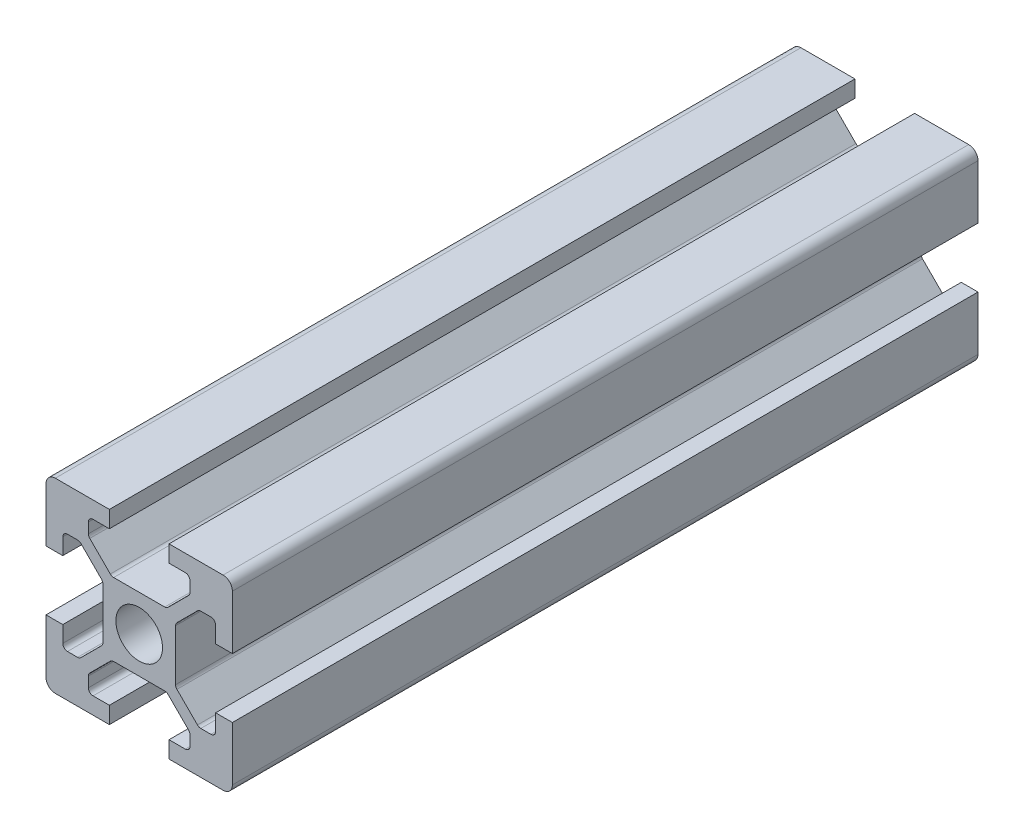
SolidWorks part; units mm, degrees
material "1060 Alloy"
ref_plane "Front Plane" through (0, 0, 0) normal (0, 0, 1) x (1, 0, 0)
ref_plane "Top Plane" through (0, 0, 0) normal (0, 1, 0) x (1, 0, 0)
ref_plane "Right Plane" through (0, 0, 0) normal (1, 0, 0) x (0, 0, -1)
sketch "Sketch1" plane through (0, 0, 0) normal (0, 0, 1) x (1, 0, 0)
  line L0 (20, 0) -> (-8.059, 28.059) construction
  line L1 (0, 0) -> (6.8, 0)
  line L2 (0, 0) -> (0, 6.8)
  line L3 (0, 20) -> (6.8, 20)
  line L4 (20, 0) -> (20, 6.8)
  line L5 (6.8, 20) -> (6.8, 18.2)
  line L6 (20, 20) -> (8.2322, 8.2322) construction
  line L7 (12.95, 6.1) -> (7.05, 6.1)
  line L8 (13.9, 7.05) -> (13.9, 12.95)
  line L9 (12.95, 13.9) -> (7.05, 13.9)
  line L10 (6.1, 7.05) -> (6.1, 12.95)
  line L11 (13.9, 6.1) -> (6.1, 13.9) construction
  line L12 (13.9, 13.9) -> (6.1, 6.1) construction
  line L13 (4.55, 16.4) -> (7.05, 13.9)
  line L14 (13.2, 18.2) -> (13.2, 20)
  line L15 (1.8, 6.8) -> (0, 6.8)
  line L16 (0, 13.2) -> (0, 20)
  line L17 (0, 13.2) -> (1.8, 13.2)
  line L18 (10, 10) -> (10, 13.9) construction
  line L19 (16.4, 4.55) -> (13.9, 7.05)
  line L20 (4.55, 16.4) -> (4.55, 18.2)
  line L21 (4.55, 18.2) -> (6.8, 18.2)
  line L22 (13.2, 18.2) -> (15.45, 18.2)
  line L23 (15.45, 18.2) -> (15.45, 16.4)
  line L24 (15.45, 16.4) -> (12.95, 13.9)
  line L25 (16.4, 4.55) -> (18.2, 4.55)
  line L26 (18.2, 4.55) -> (18.2, 6.8)
  line L27 (20, 6.8) -> (18.2, 6.8)
  line L28 (18.2, 13.2) -> (20, 13.2)
  line L29 (18.2, 13.2) -> (18.2, 15.45)
  line L30 (18.2, 15.45) -> (16.4, 15.45)
  line L31 (16.4, 15.45) -> (13.9, 12.95)
  line L32 (1.8, 4.55) -> (3.6, 4.55)
  line L33 (3.6, 15.45) -> (6.1, 12.95)
  line L34 (3.6, 15.45) -> (1.8, 15.45)
  line L35 (1.8, 15.45) -> (1.8, 13.2)
  line L36 (0, 13.2) -> (1.8, 13.2)
  line L37 (1.8, 6.8) -> (0, 6.8)
  line L38 (3.6, 4.55) -> (6.1, 7.05)
  line L39 (1.8, 6.8) -> (1.8, 4.55)
  line L40 (15.45, 3.6) -> (12.95, 6.1)
  line L41 (4.55, 3.6) -> (7.05, 6.1)
  line L42 (4.55, 1.8) -> (4.55, 3.6)
  line L43 (6.8, 1.8) -> (4.55, 1.8)
  line L44 (6.8, 1.8) -> (6.8, 0)
  line L45 (15.45, 3.6) -> (15.45, 1.8)
  line L46 (15.45, 1.8) -> (13.2, 1.8)
  line L47 (13.2, 0) -> (13.2, 1.8)
  line L48 (13.2, 20) -> (20, 20)
  line L49 (20, 13.2) -> (20, 20)
  line L50 (13.2, 0) -> (20, 0)
  line L51 (6.1, 6.1) -> (-5.5045, -5.5045) construction
  circle A0 centre (10, 10) radius 2.5
  point P25 (10, 16.4)
  point P39 (13.2, 19.1)
  point P46 (0.9, 6.8)
  dimension "D3" = 5
  dimension "D2" = 20
  dimension "D4" = 7.8
  dimension "D5" = 7.8
  dimension "D6" = 6.8
  dimension "D7" = 6.8
  dimension "D8" = 1.8
  dimension "D9" = 10.9
  dimension "D10" = 1.8
  dimension "D11" = 10.9
  dimension "D12" = 20
extrude "Boss-Extrude1" add sketch "Sketch1" along normal blind 80 contours L47 L50 L4 L27 L26 L25 L19 L8 L31 L30 L29 L28 L49 L48 L14 L22 L23 L24 L9 L13 L20 L21 L5 L3 L16 L17 L35 L34 L33 L10 L38 L32 L39 L15 L2 L1 L44 L43 L42 L41 L7 L40 L45 L46 A0
fillet "Fillet1" radius 1 4 edges at (20, 20, 40) (20, 0, 40) (0, 0, 40) (0, 20, 40)
fillet "Fillet2" radius 0.5 6 edges at (4.55, 18.2, 40) (4.55, 16.4, 40) (7.05, 13.9, 40) (15.45, 18.2, 40) (15.45, 16.4, 40) (12.95, 13.9, 40)
fillet "Fillet3" radius 0.5 6 edges at (18.2, 15.45, 40) (16.4, 15.45, 40) (13.9, 12.95, 40) (18.2, 4.55, 40) (13.9, 7.05, 40) (16.4, 4.55, 40)
fillet "Fillet4" radius 0.5 6 edges at (1.8, 15.45, 40) (3.6, 15.45, 40) (6.1, 12.95, 40) (3.6, 4.55, 40) (1.8, 4.55, 40) (6.1, 7.05, 40)
fillet "Fillet5" radius 0.5 6 edges at (7.05, 6.1, 40) (4.55, 3.6, 40) (4.55, 1.8, 40) (15.45, 1.8, 40) (15.45, 3.6, 40) (12.95, 6.1, 40)
sketch "Sketch2" plane through (0, 0, 0) normal (1, 0, 0) x (0, 0, -1)
  line L0 (-80, 10) -> (0, 10) construction
  line L1 (-80, 7.2571) -> (-80, 12.7429) construction
  line L2 (0, 11) -> (0, -11) construction
  circle A0 centre (-65.9, 10) radius 2.5
  circle A1 centre (-14.1, 10) radius 2.5
  dimension "D1" = 5
  dimension "D3" = 5
  dimension "D2" = 14.1
  dimension "D4" = 14.1
extrude "Cut-Extrude1" cut sketch "Sketch2" along normal through all both and the other way through all
